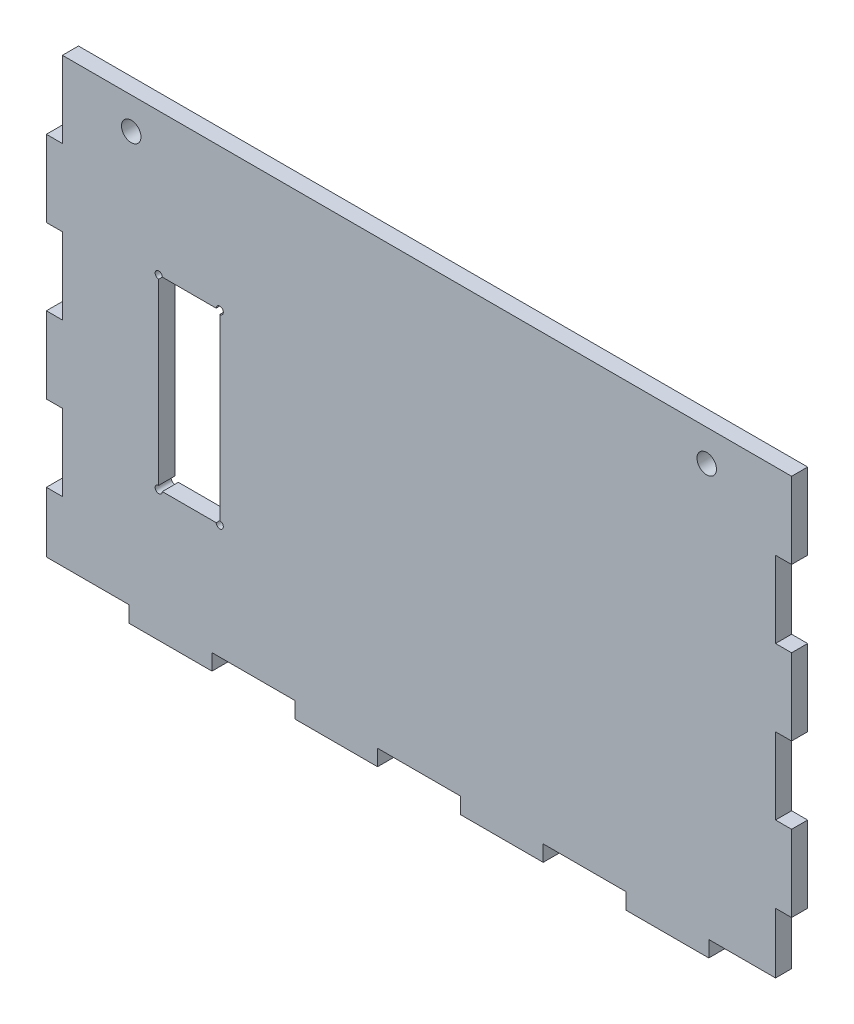
SolidWorks part; units mm, degrees
material "Acrylic (Medium-high impact)"
ref_plane "Front Plane" through (0, 0, 0) normal (0, 0, 1) x (1, 0, 0)
ref_plane "Top Plane" through (0, 0, 0) normal (0, 1, 0) x (1, 0, 0)
ref_plane "Right Plane" through (0, 0, 0) normal (1, 0, 0) x (0, 0, -1)
sketch "Sketch1" plane through (0, 0, 0) normal (0, 0, 1) x (1, 0, 0)
  line L1 (0, 0) -> (130, 0)
  line L2 (0, 0) -> (0, 80)
  line L3 (0, 80) -> (130, 80)
  line L4 (130, 0) -> (130, 80)
  dimension "D1" = 130
  dimension "D2" = 80
extrude "Boss-Extrude1" add sketch "Sketch1" along normal blind 2.8
sketch "Sketch2" plane through (0, 0, 2.8) normal (0, 0, 1) x (1, 0, 0)
  line L61 (14.4444, 2.8) -> (28.8889, 2.8) construction
  line L62 (0, 0) -> (14.4444, 0)
  line L67 (0, 0) -> (0, 2.8)
  line L72 (0, 2.8) -> (14.4444, 2.8)
  line L77 (14.4444, 0) -> (14.4444, 2.8)
  line L97 (28.8889, 0) -> (28.8889, 2.8)
  line L98 (28.8889, 0) -> (43.3333, 0)
  line L107 (43.3333, 0) -> (43.3333, 2.8)
  line L115 (28.8889, 2.8) -> (43.3333, 2.8)
  line L117 (43.3333, 2.8) -> (57.7778, 2.8) construction
  line L123 (57.7778, 0) -> (57.7778, 2.8)
  line L128 (57.7778, 0) -> (72.2222, 0)
  line L129 (72.2222, 0) -> (72.2222, 2.8)
  line L131 (57.7778, 2.8) -> (72.2222, 2.8)
  line L132 (72.2222, 2.8) -> (86.6667, 2.8) construction
  line L133 (86.6667, 0) -> (86.6667, 2.8)
  line L134 (86.6667, 0) -> (101.1111, 0)
  line L135 (101.1111, 0) -> (101.1111, 2.8)
  line L136 (86.6667, 2.8) -> (101.1111, 2.8)
  line L137 (101.1111, 2.8) -> (115.5556, 2.8) construction
  line L138 (115.5556, 0) -> (115.5556, 2.8)
  line L139 (115.5556, 0) -> (130, 0)
  line L142 (130, 0) -> (130, 80) construction
  line L143 (0, 80) -> (0, 0) construction
  line L144 (0, 13.3333) -> (2.8, 13.3333)
  line L145 (0, 13.3333) -> (0, 26.6667)
  line L146 (130, 2.8) -> (144.4444, 2.8) construction
  line L147 (0, 26.6667) -> (2.8, 26.6667)
  line L148 (2.8, 13.3333) -> (2.8, 26.6667)
  line L149 (2.8, 13.3333) -> (2.8, 0) construction
  line L150 (0, 40) -> (0, 53.3333)
  line L151 (0, 40) -> (2.8, 40)
  line L152 (2.8, 40) -> (2.8, 53.3333)
  line L153 (0, 53.3333) -> (2.8, 53.3333)
  line L154 (2.8, 40) -> (2.8, 26.6667) construction
  line L155 (0, 66.6667) -> (0, 80)
  line L156 (0, 66.6667) -> (2.8, 66.6667)
  line L157 (2.8, 66.6667) -> (2.8, 80)
  line L158 (0, 80) -> (2.8, 80)
  line L159 (2.8, 66.6667) -> (2.8, 53.3333) construction
  line L160 (130, 80) -> (0, 80) construction
  line L161 (127.2, 80) -> (127.2, 66.6667) construction
  line L162 (127.2, 40) -> (127.2, 26.6667)
  line L163 (127.2, 66.6667) -> (130, 66.6667)
  line L164 (127.2, 66.6667) -> (127.2, 53.3333)
  line L165 (127.2, 53.3333) -> (130, 53.3333)
  line L166 (130, 66.6667) -> (130, 53.3333)
  line L167 (127.2, 40) -> (130, 40)
  line L168 (130, 40) -> (130, 26.6667)
  line L169 (127.2, 26.6667) -> (130, 26.6667)
  line L170 (127.2, 53.3333) -> (127.2, 40) construction
  line L172 (127.2, 13.3333) -> (130, 13.3333)
  line L173 (130, 13.3333) -> (130, 0)
  line L175 (127.2, 26.6667) -> (127.2, 13.3333) construction
  line L183 (115.5556, 2.8) -> (130, 2.8) [skipped]
  line L184 (130, 0) -> (130, 2.8) [skipped]
  line L185 (127.2, 13.3333) -> (127.2, 2.8)
  line L186 (127.2, 2.8) -> (115.5556, 2.8)
  line L187 (127.2, 0) -> (130, 0) [skipped]
  line L188 (127.2, 13.3333) -> (127.2, 0) [skipped]
  dimension "D2" = 2.8
  dimension "D4" = 2.8
  dimension "D6" = 2.8
  dimension "D1" = 5
  dimension "D3" = 3
  dimension "D5" = 3
extrude "Cut-Extrude1" cut sketch "Sketch2" against normal through all
sketch "Sketch3" plane through (0, 0, 2.8) normal (0, 0, 1) x (1, 0, 0)
  line L0 (0, 66.6667) -> (0, 53.3333) construction
  line L1 (130, 80) -> (2.8, 80) construction
  line L2 (0, 66.6667) -> (130, 66.6667) construction
  line L3 (65, 66.6667) -> (65, 50066.6667) construction
  circle A0 centre (14.8, 74.5) radius 1.7
  circle A1 centre (115.2, 74.5) radius 1.7
  point P10 (65, 66.6667)
  dimension "D1" = 3.4
  dimension "D2" = 14.8
  dimension "D3" = 5.5
extrude "Cut-Extrude2" cut sketch "Sketch3" against normal up to next
sketch "Sketch4" plane through (0, 0, 0) normal (0, 0, -1) x (-1, 0, 0)
  line L0 (-2.8, 13.3333) -> (-2.8, 26.6667) construction
  line L1 (-29.625, 55.2) -> (-20.225, 55.2)
  line L2 (-30.25, 54.575) -> (-30.25, 23.425)
  line L3 (-29.625, 22.8) -> (-20.225, 22.8)
  line L4 (-19.6, 54.575) -> (-19.6, 23.425)
  line L5 (-43.3333, 2.8) -> (-28.8889, 2.8) construction
  arc A0 (-30.25, 23.425) -> (-29.625, 22.8) centre (-30.25, 22.8) ccw
  arc A1 (-20.225, 22.8) -> (-19.6, 23.425) centre (-19.6, 22.8) ccw
  arc A2 (-19.6, 54.575) -> (-20.225, 55.2) centre (-19.6, 55.2) ccw
  arc A3 (-29.625, 55.2) -> (-30.25, 54.575) centre (-30.25, 55.2) ccw
  dimension "D3" = 1.25
  dimension "D1" = 10.65
  dimension "D2" = 32.4
  dimension "D4" = 16.8
  dimension "D5" = 20
extrude "Cut-Extrude3" cut sketch "Sketch4" against normal up to next
other "Width tolerance" face at (1.4, 26.6667, 1.4) face at (1.4, 53.3333, 1.4) face at (1.4, 66.6667, 1.4) face at (1.4, 40, 1.4) face at (1.4, 13.3333, 1.4) face at (128.6, 66.6667, 1.4) face at (128.6, 40, 1.4) face at (128.6, 53.3333, 1.4) face at (128.6, 26.6667, 1.4) face at (128.6, 13.3333, 1.4) face at (101.1111, 1.4, 1.4) face at (115.5556, 1.4, 1.4) face at (86.6667, 1.4, 1.4) face at (72.2222, 1.4, 1.4) face at (43.3333, 1.4, 1.4) face at (57.7778, 1.4, 1.4) face at (28.8889, 1.4, 1.4) face at (14.4444, 1.4, 1.4) parameters "D1"=0
equation "\"wall_thickness\" = 2.8mm"
equation "\"D1@Boss-Extrude1\"=\"wall_thickness\""
equation "\"slot_width_tolerance\"= 0.0mm"
equation "\"slot_depth\"= 2.8mm"
equation "\"D2@Sketch2\"=\"slot_depth\""
equation "\"D4@Sketch2\"=\"slot_depth\""
equation "\"D6@Sketch2\"=\"slot_depth\""
equation "\"D2@Sketch3\"=12.00mm+\"slot_depth\""
equation "\"D1@Width tolerance\"=\"slot_width_tolerance\""
